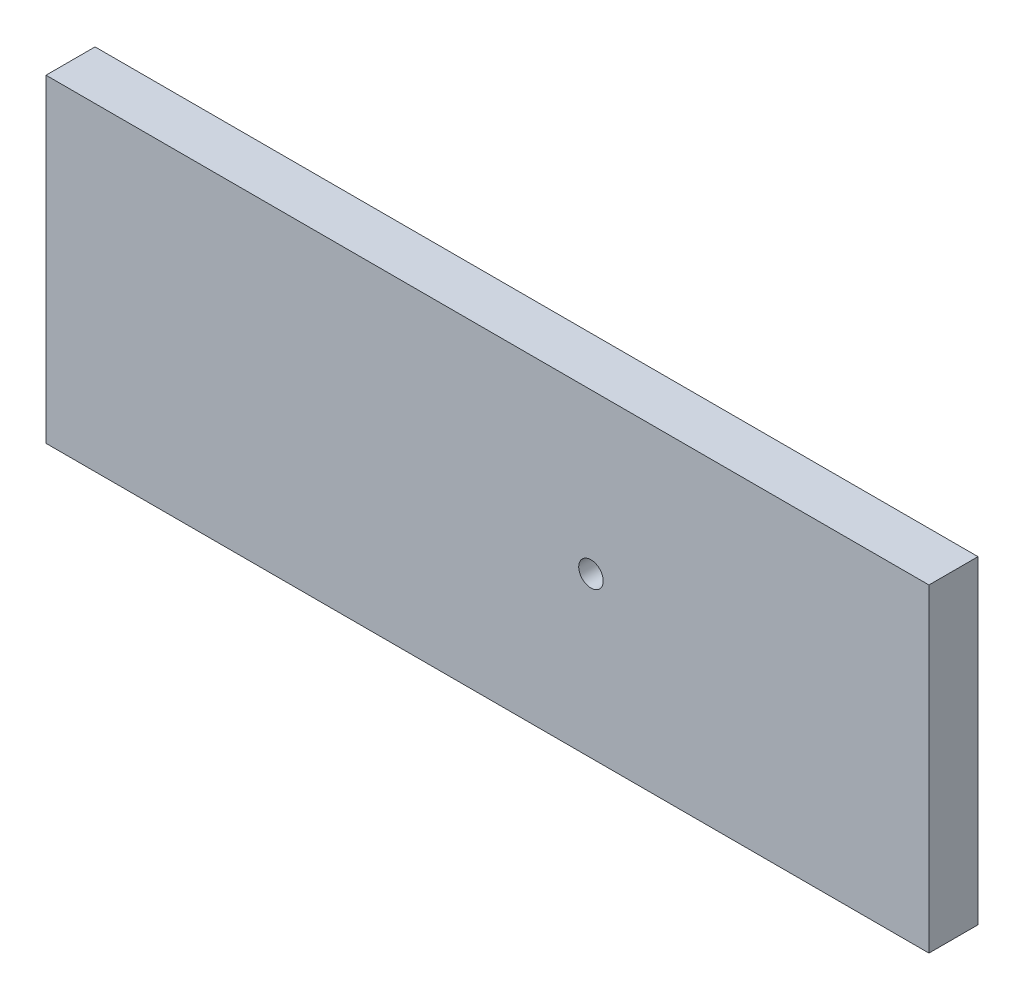
SolidWorks part; units mm, degrees
ref_plane "Plan de face" through (0, 0, 0) normal (0, 0, 1) x (1, 0, 0)
ref_plane "Plan de dessus" through (0, 0, 0) normal (0, 1, 0) x (1, 0, 0)
ref_plane "Plan de droite" through (0, 0, 0) normal (1, 0, 0) x (0, 0, -1)
sketch "Esquisse1" plane through (0, 0, 0) normal (0, 0, 1) x (1, 0, 0)
  line L0 (26.8, 41.275) -> (26.8, -41.275) construction
  line L1 (-114.3, 41.275) -> (114.3, 41.275)
  line L2 (-114.3, 41.275) -> (-114.3, -41.275)
  line L3 (-114.3, -41.275) -> (114.3, -41.275)
  line L4 (114.3, 41.275) -> (114.3, -41.275)
  line L5 (-114.3, 41.275) -> (114.3, -41.275) construction
  line L6 (-114.3, -41.275) -> (114.3, 41.275) construction
  line L7 (0, 0) -> (26.8, 0) construction
  circle A6 centre (26.8, 0) radius 3.175
  point P0 (0, 0)
  dimension "D4" = 6.35
  dimension "D1" = 82.55
  dimension "D2" = 228.6
  dimension "D3" = 87.5
extrude "Boss.-Extru.1" add sketch "Esquisse1" along normal blind 12.7
